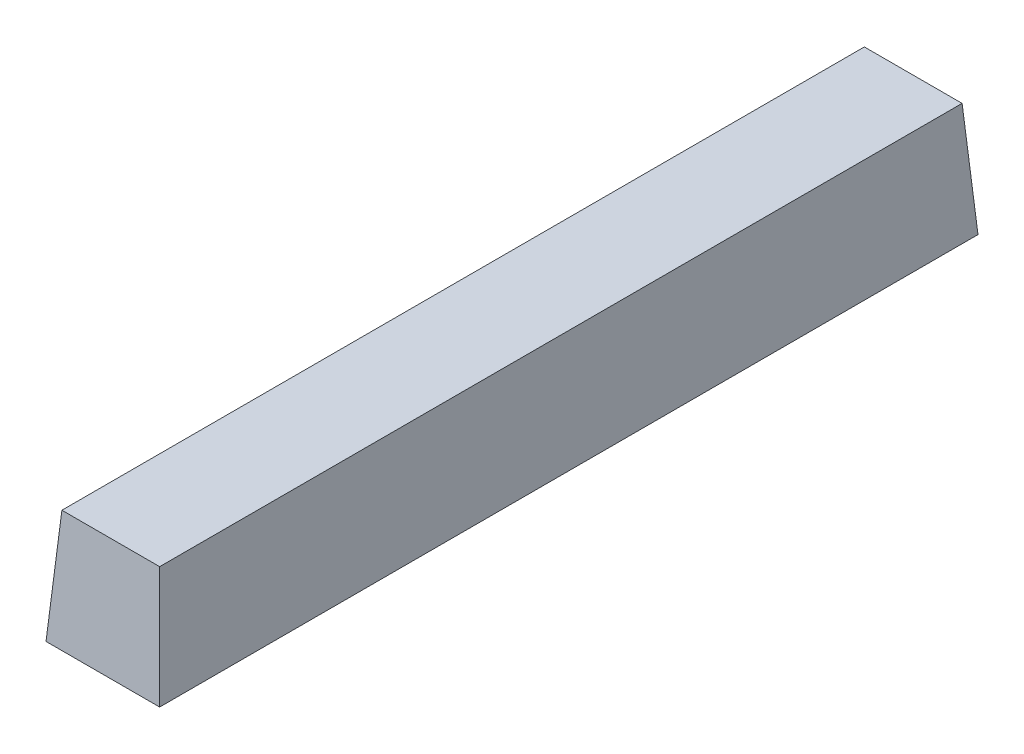
SolidWorks part; units mm, degrees
ref_plane "Front Plane" through (0, 0, 0) normal (0, 0, 1) x (1, 0, 0)
ref_plane "Top Plane" through (0, 0, 0) normal (0, 1, 0) x (1, 0, 0)
ref_plane "Right Plane" through (0, 0, 0) normal (1, 0, 0) x (0, 0, -1)
sketch "Sketch3" plane through (0, 0, 0) normal (0, 1, 0) x (1, 0, 0)
  line L1 (0, 0) -> (22, 0) construction
  line L2 (0, 0) -> (0, -112) construction
  line L3 (0, -112) -> (22, -112) construction
  line L4 (22, 0) -> (22, -112) construction
  dimension "D1" = 22
  dimension "D2" = 112
sketch "Sketch1" plane through (0, 0, 0) normal (0, 1, 0) x (1, 0, 0)
  line L0 (0, -112) -> (22, -112) construction
  line L1 (0, 0) -> (10, 0)
  line L2 (0, 0) -> (0, -72)
  line L3 (0, -72) -> (10, -72)
  line L4 (10, 0) -> (10, -72)
  dimension "D1" = 10
  dimension "D2" = 40
extrude "Boss-Extrude1" add sketch "Sketch1" along normal blind 10 draft 4
ref_plane "Plane4" through (5, 0, 0) normal (1, 0, 0) x (0, 0, -1)
